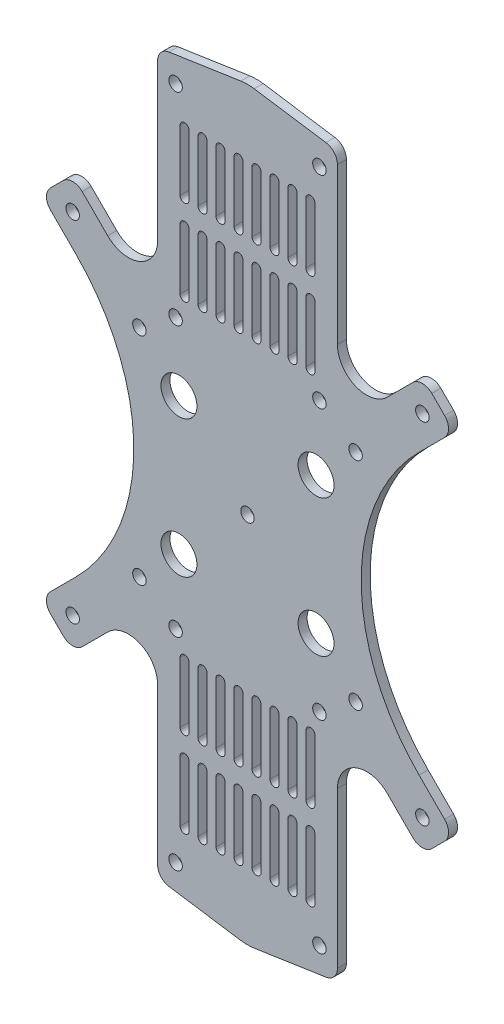
SolidWorks part; units mm, degrees
ref_plane "Alzado" through (0, 0, 0) normal (0, 0, 1) x (1, 0, 0)
ref_plane "Planta" through (0, 0, 0) normal (0, 1, 0) x (1, 0, 0)
ref_plane "Vista lateral" through (0, 0, 0) normal (1, 0, 0) x (0, 0, -1)
sketch "Croquis1" plane through (0, 0, 0) normal (0, 0, 1) x (1, 0, 0)
  line L0 (0, 0) -> (27.8544, 27.8544) construction
  line L1 (0, 0) -> (-42.4264, 42.4264) construction
  line L2 (0, 0) -> (0, 42.4264) construction
  line L3 (15.25, -15.25) -> (-15.25, -15.25) construction
  line L4 (15.25, -15.25) -> (15.25, 15.25) construction
  line L5 (15.25, 15.25) -> (-15.25, 15.25) construction
  line L6 (-15.25, -15.25) -> (-15.25, 15.25) construction
  line L7 (15.25, -15.25) -> (-15.25, 15.25) construction
  line L8 (15.25, 15.25) -> (-15.25, -15.25) construction
  line L9 (0, 42.4264) -> (-20, 42.4264) construction
  line L10 (-42.4264, 42.4264) -> (-38.8909, 45.9619)
  line L11 (-38.8909, 45.9619) -> (-31.0962, 38.1673)
  line L12 (-20, 42.7635) -> (-20, 80)
  line L13 (-42.4264, 42.4264) -> (-45.9619, 38.8909)
  line L14 (-45.9619, 38.8909) -> (-38.1673, 31.0962)
  line L15 (20, 42.7635) -> (20, 80)
  line L16 (38.8909, 45.9619) -> (31.0962, 38.1673)
  line L17 (42.4264, 42.4264) -> (38.8909, 45.9619)
  line L18 (42.4264, 42.4264) -> (45.9619, 38.8909)
  line L19 (-45.9619, -38.8909) -> (-38.1673, -31.0962)
  line L20 (0, 0) -> (-15.25, 0) construction
  line L21 (45.9619, 38.8909) -> (38.1673, 31.0962)
  line L22 (42.4264, -42.4264) -> (45.9619, -38.8909)
  line L23 (42.4264, -42.4264) -> (38.8909, -45.9619)
  line L24 (38.8909, -45.9619) -> (31.0962, -38.1673)
  line L25 (20, -42.7635) -> (20, -80)
  line L26 (-20, -42.7635) -> (-20, -80)
  line L27 (-38.8909, -45.9619) -> (-31.0962, -38.1673)
  line L28 (-42.4264, -42.4264) -> (-38.8909, -45.9619)
  line L29 (-42.4264, -42.4264) -> (-45.9619, -38.8909)
  line L30 (45.9619, -38.8909) -> (38.1673, -31.0962)
  line L31 (-20, 80) -> (20, 80) construction
  line L32 (0, 80) -> (0, 83) construction
  line L33 (-20, 80) -> (0, 83)
  line L34 (0, 83) -> (20, 80)
  line L35 (0, -80) -> (0, -83) construction
  line L36 (-20, -80) -> (20, -80) construction
  line L37 (0, -83) -> (20, -80)
  line L38 (-20, -80) -> (0, -83)
  line L39 (-11, -54) -> (-11, -67.5)
  line L41 (-15, -54) -> (-15, -67.5)
  line L43 (-13, -54) -> (-13, -67.5)
  line L44 (-9, -54) -> (-9, -67.5)
  line L45 (-7, -54) -> (-7, -67.5)
  line L46 (-5, -54) -> (-5, -67.5)
  line L47 (-3, -54) -> (-3, -67.5)
  line L48 (-1, -54) -> (-1, -67.5)
  line L49 (1, -54) -> (1, -67.5)
  line L50 (3, -54) -> (3, -67.5)
  line L51 (5, -54) -> (5, -67.5)
  line L52 (7, -54) -> (7, -67.5)
  line L53 (9, -54) -> (9, -67.5)
  line L54 (11, -54) -> (11, -67.5)
  line L55 (13, -54) -> (13, -67.5)
  line L56 (15, -54) -> (15, -67.5)
  line L57 (-11, -35) -> (-11, -48.5)
  line L58 (-9, -35) -> (-9, -48.5)
  line L59 (-7, -35) -> (-7, -48.5)
  line L60 (-5, -35) -> (-5, -48.5)
  line L61 (-3, -35) -> (-3, -48.5)
  line L62 (-1, -35) -> (-1, -48.5)
  line L63 (1, -35) -> (1, -48.5)
  line L64 (3, -35) -> (3, -48.5)
  line L65 (5, -35) -> (5, -48.5)
  line L66 (7, -35) -> (7, -48.5)
  line L67 (9, -35) -> (9, -48.5)
  line L68 (11, -35) -> (11, -48.5)
  line L69 (13, -35) -> (13, -48.5)
  line L70 (15, -35) -> (15, -48.5)
  line L71 (-15, -35) -> (-15, -48.5)
  line L72 (-13, -35) -> (-13, -48.5)
  line L73 (-15, 54) -> (-15, 67.5)
  line L74 (-13, 35) -> (-13, 48.5)
  line L75 (-15, 35) -> (-15, 48.5)
  line L76 (15, 35) -> (15, 48.5)
  line L77 (13, 35) -> (13, 48.5)
  line L78 (11, 35) -> (11, 48.5)
  line L79 (9, 35) -> (9, 48.5)
  line L80 (7, 35) -> (7, 48.5)
  line L81 (5, 35) -> (5, 48.5)
  line L82 (3, 35) -> (3, 48.5)
  line L83 (1, 35) -> (1, 48.5)
  line L84 (-1, 35) -> (-1, 48.5)
  line L85 (-3, 35) -> (-3, 48.5)
  line L86 (-5, 35) -> (-5, 48.5)
  line L87 (-7, 35) -> (-7, 48.5)
  line L88 (-9, 35) -> (-9, 48.5)
  line L89 (-11, 35) -> (-11, 48.5)
  line L90 (15, 54) -> (15, 67.5)
  line L91 (13, 54) -> (13, 67.5)
  line L92 (11, 54) -> (11, 67.5)
  line L93 (9, 54) -> (9, 67.5)
  line L94 (7, 54) -> (7, 67.5)
  line L95 (5, 54) -> (5, 67.5)
  line L96 (3, 54) -> (3, 67.5)
  line L97 (1, 54) -> (1, 67.5)
  line L98 (-1, 54) -> (-1, 67.5)
  line L99 (-3, 54) -> (-3, 67.5)
  line L100 (-5, 54) -> (-5, 67.5)
  line L101 (-7, 54) -> (-7, 67.5)
  line L102 (-9, 54) -> (-9, 67.5)
  line L103 (-13, 54) -> (-13, 67.5)
  line L104 (-11, 54) -> (-11, 67.5)
  circle A0 centre (-15.25, 15.25) radius 4
  circle A1 centre (-24.0416, 24.0416) radius 1.5
  circle A2 centre (-38.8909, 38.8909) radius 1.5
  arc A3 (-31.0962, 38.1673) -> (-20, 42.7635) centre (-26.5, 42.7635) ccw
  arc A4 (31.0962, 38.1673) -> (20, 42.7635) centre (26.5, 42.7635) cw
  circle A5 centre (38.8909, 38.8909) radius 1.5
  circle A6 centre (24.0416, 24.0416) radius 1.5
  circle A7 centre (15.25, 15.25) radius 4
  circle A8 centre (15.25, -15.25) radius 4
  circle A9 centre (24.0416, -24.0416) radius 1.5
  circle A10 centre (38.8909, -38.8909) radius 1.5
  arc A11 (31.0962, -38.1673) -> (20, -42.7635) centre (26.5, -42.7635) ccw
  circle A12 centre (-15.25, -15.25) radius 4
  circle A13 centre (-24.0416, -24.0416) radius 1.5
  circle A14 centre (-38.8909, -38.8909) radius 1.5
  arc A15 (-31.0962, -38.1673) -> (-20, -42.7635) centre (-26.5, -42.7635) cw
  arc A16 (-38.1673, -31.0962) -> (-38.1673, 31.0962) centre (-69.2635, 0) ccw
  arc A17 (38.1673, -31.0962) -> (38.1673, 31.0962) centre (69.2635, 0) cw
  circle A18 centre (0, 0) radius 1.5
  circle A19 centre (-16, -75) radius 1.5
  circle A20 centre (-16, -30) radius 1.5
  circle A21 centre (-16, 30) radius 1.5
  circle A22 centre (-16, 75) radius 1.5
  circle A23 centre (16, -75) radius 1.5
  circle A24 centre (16, -30) radius 1.5
  circle A25 centre (16, 30) radius 1.5
  circle A26 centre (16, 75) radius 1.5
  arc A27 (-15, -54) -> (-13, -54) centre (-14, -54) cw
  arc A28 (-15, -67.5) -> (-13, -67.5) centre (-14, -67.5) ccw
  arc A29 (-11, -54) -> (-9, -54) centre (-10, -54) cw
  arc A30 (-11, -67.5) -> (-9, -67.5) centre (-10, -67.5) ccw
  arc A31 (-7, -54) -> (-5, -54) centre (-6, -54) cw
  arc A32 (-7, -67.5) -> (-5, -67.5) centre (-6, -67.5) ccw
  arc A33 (-3, -54) -> (-1, -54) centre (-2, -54) cw
  arc A34 (-3, -67.5) -> (-1, -67.5) centre (-2, -67.5) ccw
  arc A35 (1, -54) -> (3, -54) centre (2, -54) cw
  arc A36 (1, -67.5) -> (3, -67.5) centre (2, -67.5) ccw
  arc A37 (5, -54) -> (7, -54) centre (6, -54) cw
  arc A38 (5, -67.5) -> (7, -67.5) centre (6, -67.5) ccw
  arc A39 (9, -54) -> (11, -54) centre (10, -54) cw
  arc A40 (9, -67.5) -> (11, -67.5) centre (10, -67.5) ccw
  arc A41 (13, -54) -> (15, -54) centre (14, -54) cw
  arc A42 (13, -67.5) -> (15, -67.5) centre (14, -67.5) ccw
  arc A43 (-11, -35) -> (-9, -35) centre (-10, -35) cw
  arc A44 (-11, -48.5) -> (-9, -48.5) centre (-10, -48.5) ccw
  arc A45 (-7, -35) -> (-5, -35) centre (-6, -35) cw
  arc A46 (-7, -48.5) -> (-5, -48.5) centre (-6, -48.5) ccw
  arc A47 (-3, -35) -> (-1, -35) centre (-2, -35) cw
  arc A48 (-3, -48.5) -> (-1, -48.5) centre (-2, -48.5) ccw
  arc A49 (1, -35) -> (3, -35) centre (2, -35) cw
  arc A50 (1, -48.5) -> (3, -48.5) centre (2, -48.5) ccw
  arc A51 (5, -35) -> (7, -35) centre (6, -35) cw
  arc A52 (5, -48.5) -> (7, -48.5) centre (6, -48.5) ccw
  arc A53 (9, -35) -> (11, -35) centre (10, -35) cw
  arc A54 (9, -48.5) -> (11, -48.5) centre (10, -48.5) ccw
  arc A55 (13, -35) -> (15, -35) centre (14, -35) cw
  arc A56 (13, -48.5) -> (15, -48.5) centre (14, -48.5) ccw
  arc A57 (-15, -35) -> (-13, -35) centre (-14, -35) cw
  arc A58 (-15, -48.5) -> (-13, -48.5) centre (-14, -48.5) ccw
  arc A59 (-15, 48.5) -> (-13, 48.5) centre (-14, 48.5) cw
  arc A60 (-15, 35) -> (-13, 35) centre (-14, 35) ccw
  arc A61 (13, 48.5) -> (15, 48.5) centre (14, 48.5) cw
  arc A62 (13, 35) -> (15, 35) centre (14, 35) ccw
  arc A63 (9, 48.5) -> (11, 48.5) centre (10, 48.5) cw
  arc A64 (9, 35) -> (11, 35) centre (10, 35) ccw
  arc A65 (5, 48.5) -> (7, 48.5) centre (6, 48.5) cw
  arc A66 (5, 35) -> (7, 35) centre (6, 35) ccw
  arc A67 (1, 48.5) -> (3, 48.5) centre (2, 48.5) cw
  arc A68 (1, 35) -> (3, 35) centre (2, 35) ccw
  arc A69 (-3, 48.5) -> (-1, 48.5) centre (-2, 48.5) cw
  arc A70 (-3, 35) -> (-1, 35) centre (-2, 35) ccw
  arc A71 (-7, 48.5) -> (-5, 48.5) centre (-6, 48.5) cw
  arc A72 (-7, 35) -> (-5, 35) centre (-6, 35) ccw
  arc A73 (-11, 48.5) -> (-9, 48.5) centre (-10, 48.5) cw
  arc A74 (-11, 35) -> (-9, 35) centre (-10, 35) ccw
  arc A75 (13, 67.5) -> (15, 67.5) centre (14, 67.5) cw
  arc A76 (13, 54) -> (15, 54) centre (14, 54) ccw
  arc A77 (9, 67.5) -> (11, 67.5) centre (10, 67.5) cw
  arc A78 (9, 54) -> (11, 54) centre (10, 54) ccw
  arc A79 (5, 67.5) -> (7, 67.5) centre (6, 67.5) cw
  arc A80 (5, 54) -> (7, 54) centre (6, 54) ccw
  arc A81 (1, 67.5) -> (3, 67.5) centre (2, 67.5) cw
  arc A82 (1, 54) -> (3, 54) centre (2, 54) ccw
  arc A83 (-3, 67.5) -> (-1, 67.5) centre (-2, 67.5) cw
  arc A84 (-3, 54) -> (-1, 54) centre (-2, 54) ccw
  arc A85 (-7, 67.5) -> (-5, 67.5) centre (-6, 67.5) cw
  arc A86 (-7, 54) -> (-5, 54) centre (-6, 54) ccw
  arc A87 (-11, 67.5) -> (-9, 67.5) centre (-10, 67.5) cw
  arc A88 (-11, 54) -> (-9, 54) centre (-10, 54) ccw
  arc A89 (-15, 67.5) -> (-13, 67.5) centre (-14, 67.5) cw
  arc A90 (-15, 54) -> (-13, 54) centre (-14, 54) ccw
  point P35 (-34.9935, 42.0646)
  point P37 (44.1942, 40.6586)
  point P45 (44.1942, -40.6586)
  point P61 (-34.9935, -42.0646)
  dimension "D2" = 8
  dimension "D4" = 5
  dimension "D8" = 6.5
  dimension "D10" = 3
  dimension "D11" = 3
  dimension "D13" = 4
  dimension "D15" = 3
  dimension "D16" = 3
  dimension "D18" = 45
  dimension "D1" = 30.5
  dimension "D3" = 60
  dimension "D5" = 21
  dimension "D6" = 20
  dimension "D7" = 5
  dimension "D9" = 5
  dimension "D12" = 80
  dimension "D14" = 5
  dimension "D17" = 4
  dimension "D19" = 2
  dimension "D20" = 13.5
  dimension "D21" = 7.5
  dimension "D22" = 5
  dimension "D23" = 8
  dimension "D24" = 2
extrude "Saliente-Extruir1" add sketch "Croquis1" along normal blind 2
fillet "Redondeo1" radius 3 12 edges at (45.9619, -38.8909, 1) (38.8909, -45.9619, 1) (-45.9619, -38.8909, 1) (-38.8909, -45.9619, 1) (45.9619, 38.8909, 1) (38.8909, 45.9619, 1) (-38.8909, 45.9619, 1) (-45.9619, 38.8909, 1) (20, 80, 1) (-20, 80, 1) (20, -80, 1) (-20, -80, 1)
fillet "Redondeo2" radius 10 2 edges at (0, -83, 1) (0, 83, 1)
